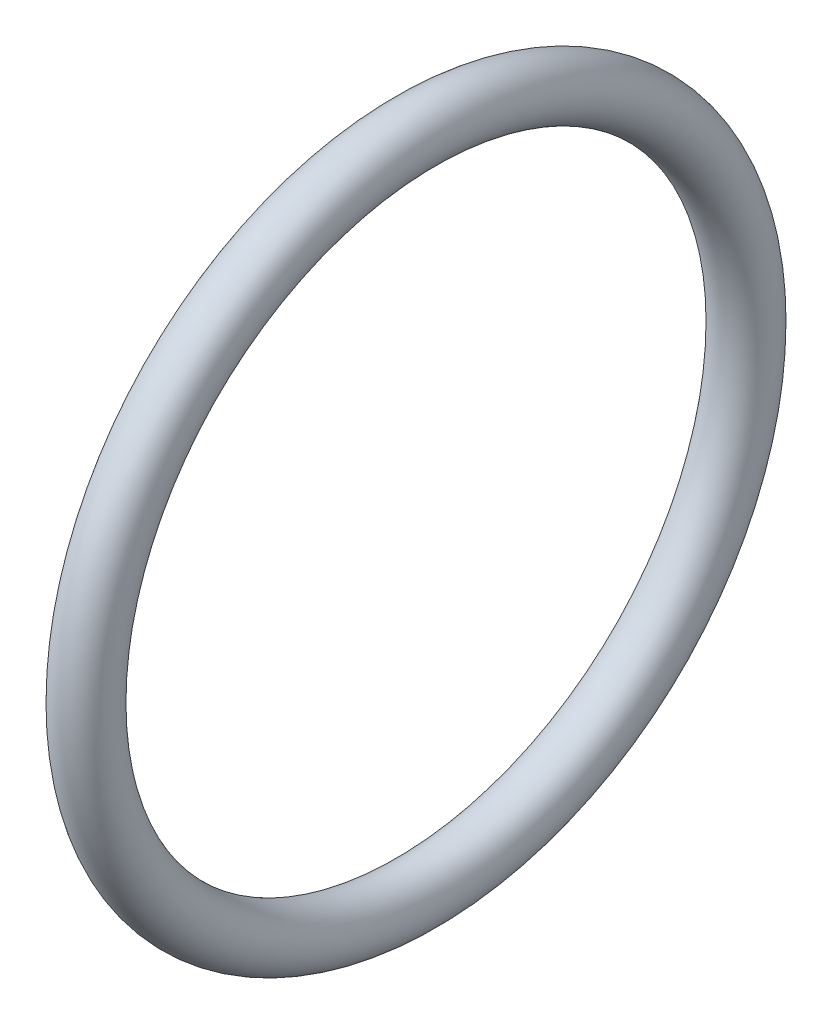
SolidWorks part; units mm, degrees
ref_plane "Front" through (0, 0, 0) normal (0, 0, 1) x (1, 0, 0)
ref_plane "Top" through (0, 0, 0) normal (0, 1, 0) x (1, 0, 0)
ref_plane "Right" through (0, 0, 0) normal (1, 0, 0) x (0, 0, -1)
sketch "Sketch1" plane through (0, 0, 0) normal (0, 0, 1) x (1, 0, 0)
  line L0 (0, 0) -> (12.8948, 0) construction
  line L1 (0, 0) -> (0, 13.125) construction
  circle A0 centre (1.125, 13.125) radius 1.125
  dimension "D1" = 2.25
  dimension "D2" = 28.5
revolve "Base-Revolve" add sketch "Sketch1" angle 360 about L0
